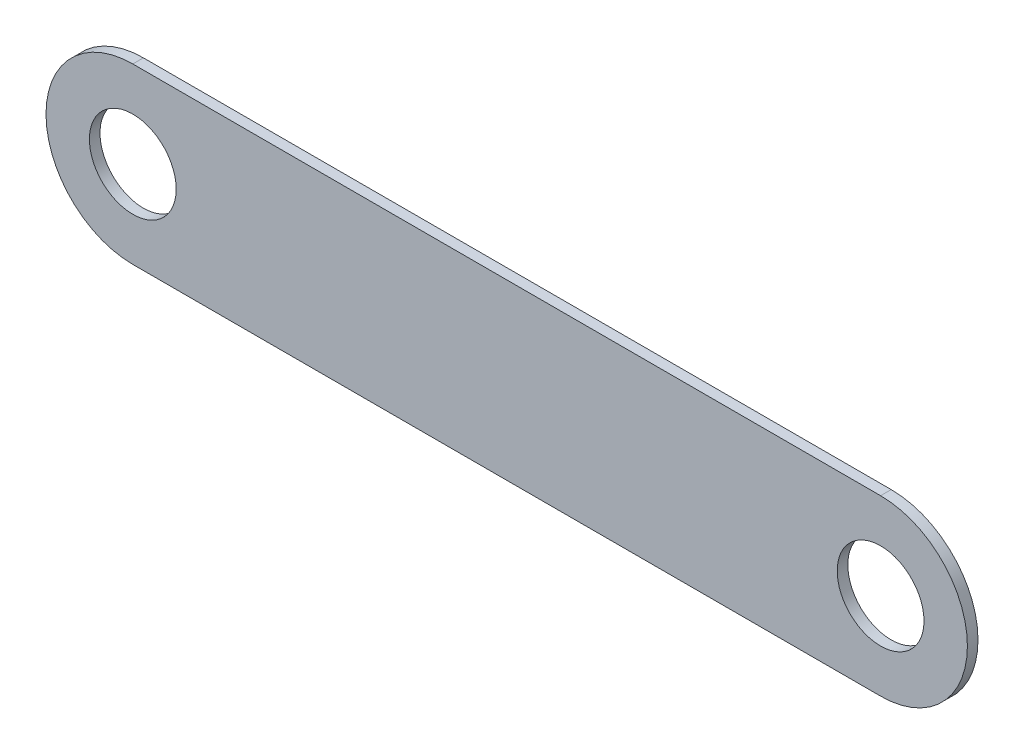
SolidWorks part; units mm, degrees
material "6061 Alloy"
ref_plane "Front Plane" through (0, 0, 0) normal (0, 0, 1) x (1, 0, 0)
ref_plane "Top Plane" through (0, 0, 0) normal (0, 1, 0) x (1, 0, 0)
ref_plane "Right Plane" through (0, 0, 0) normal (1, 0, 0) x (0, 0, -1)
sketch "Sketch1" plane through (0, 0, 0) normal (0, 0, 1) x (1, 0, 0)
  line L0 (0, 13) -> (112, 13)
  line L1 (0, -13) -> (112, -13)
  circle A0 centre (0, 0) radius 6.5
  arc A1 (0, 13) -> (0, -13) centre (0, 0) ccw
  circle A2 centre (112, 0) radius 6.5
  arc A3 (112, -13) -> (112, 13) centre (112, 0) ccw
  dimension "D1" = 112
  dimension "D2" = 13
  dimension "D3" = 26
extrude "Boss-Extrude1" add sketch "Sketch1" along normal blind 1.5875
